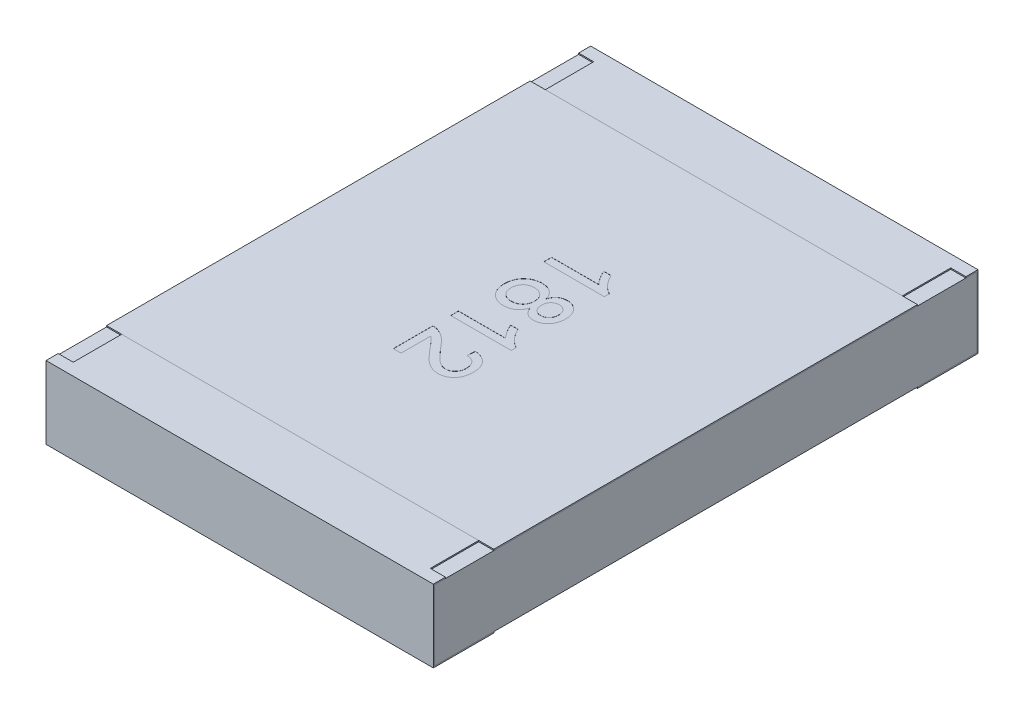
SolidWorks part; units mm, degrees
ref_plane "Front Plane" through (0, 0, 0) normal (0, 0, 1) x (1, 0, 0)
ref_plane "Top Plane" through (0, 0, 0) normal (0, 1, 0) x (1, 0, 0)
ref_plane "Right Plane" through (0, 0, 0) normal (1, 0, 0) x (0, 0, -1)
sketch "Sketch4" plane through (0, 0, 0) normal (1, 0, 0) x (0, 0, -1)
  line L0 (0, 0.1169) -> (0, -0.0721) construction
  line L1 (-2.25, 0) -> (0.3788, 0) construction
  line L2 (-2.25, 0.3) -> (-2.25, -0.3)
  line L3 (-2.25, -0.3) -> (-1.75, -0.3)
  line L4 (-1.75, 0.3) -> (-1.75, 0.29)
  line L5 (-1.75, 0.29) -> (-2.24, 0.29)
  line L6 (-2.24, 0.29) -> (-2.24, -0.29)
  line L7 (-2.24, -0.29) -> (-1.75, -0.29)
  line L8 (-1.75, -0.29) -> (-1.75, -0.3)
  line L9 (-1.75, 0.3) -> (-2.25, 0.3)
  line L10 (1.75, 0.3) -> (2.25, 0.3)
  line L11 (1.75, -0.29) -> (1.75, -0.3)
  line L12 (2.24, -0.29) -> (1.75, -0.29)
  line L13 (2.24, 0.29) -> (2.24, -0.29)
  line L14 (1.75, 0.29) -> (2.24, 0.29)
  line L15 (1.75, 0.3) -> (1.75, 0.29)
  line L16 (2.25, -0.3) -> (1.75, -0.3)
  line L17 (2.25, 0.3) -> (2.25, -0.3)
  dimension "LENGTH" = 2.25
  dimension "HEIGHT" = 0.6
  dimension "END CAP TOP LENGTH" = 0.5
  dimension "END CAP BOTTOM LENGTH" = 0.5
  dimension "D5" = 0.01
  dimension "D6" = 0.01
extrude "Boss-Extrude2" add sketch "Sketch4" along normal mid plane 3.2
sketch "Sketch5" plane through (0, 0, 0) normal (1, 0, 0) x (0, 0, -1)
  line L1 (-2.24, 0.29) -> (2.24, 0.29)
  line L2 (-2.24, 0.29) -> (-2.24, -0.29)
  line L3 (-2.24, -0.29) -> (2.24, -0.29)
  line L4 (2.24, 0.29) -> (2.24, -0.29)
extrude "Boss-Extrude3" add sketch "Sketch5" along normal up to surface and the other way up to surface separate body
sketch "Sketch6" plane through (0, 0.3, 0) normal (0, 1, 0) x (1, 0, 0)
  line L0 (-1.6, 2.25) -> (-1.6, 1.75) construction
  line L1 (-1.6, 2.15) -> (-1.475, 2.15)
  line L2 (-1.6, 2.15) -> (-1.6, 1.75)
  line L3 (-1.6, 1.75) -> (-1.475, 1.75)
  line L4 (-1.475, 2.15) -> (-1.475, 1.75)
  line L5 (1.6, 1.75) -> (-1.6, 1.75) construction
  line L6 (0, 0.0345) -> (0, -0.0345) construction
  line L7 (-0.0325, 0) -> (0.03, 0) construction
  line L8 (1.6, 2.15) -> (1.6, 1.75)
  line L9 (1.6, 1.75) -> (1.475, 1.75)
  line L10 (1.475, 2.15) -> (1.475, 1.75)
  line L11 (1.6, 2.15) -> (1.475, 2.15)
  line L12 (1.6, -2.15) -> (1.475, -2.15)
  line L13 (1.6, -2.15) -> (1.6, -1.75)
  line L14 (1.6, -1.75) -> (1.475, -1.75)
  line L15 (1.475, -2.15) -> (1.475, -1.75)
  line L16 (-1.6, -2.15) -> (-1.475, -2.15)
  line L17 (-1.6, -2.15) -> (-1.6, -1.75)
  line L18 (-1.6, -1.75) -> (-1.475, -1.75)
  line L19 (-1.475, -2.15) -> (-1.475, -1.75)
  dimension "TOP CUT WIDTH" = 0.125
  dimension "TOP CUT LENGTH" = 0.4
extrude "Cut-Extrude1" cut sketch "Sketch6" against normal up to surface (0.01 mm away) up to face at (0, 0.29, 0)
sketch "Sketch7" plane through (0, 0.29, 0) normal (0, 1, 0) x (1, 0, 0)
  line L1 (-1.6, 1.75) -> (1.6, 1.75)
  line L2 (-1.6, 1.75) -> (-1.6, -1.75)
  line L3 (-1.6, -1.75) -> (1.6, -1.75)
  line L4 (1.6, 1.75) -> (1.6, -1.75)
  line L5 (1.475, -1.75) -> (-1.475, -1.75) construction
  line L6 (1.475, 1.75) -> (-1.475, 1.75) construction
  line L7 (-1.6, -2.24) -> (-1.6, 2.24) construction
  line L8 (1.6, 2.24) -> (1.6, -2.24) construction
extrude "Boss-Extrude4" add sketch "Sketch7" along normal up to surface (0.01 mm away) separate body up to face at (0, 0.3, -2.075)
sketch "PART NUMBER" plane through (0, 0.3, 0) normal (0, 1, 0) x (1, 0, 0)
  line L0 (-0.0246, 0.1) -> (-0.0246, -0.1) construction
  line L1 (0, 0) -> (-0.0246, 0) construction
  text T0 "01005" font "Arial" height 0.05
  dimension "D1" = 0.2
sketch "Sketch8" plane through (0, 0.3, 0) normal (0, 1, 0) x (1, 0, 0)
  line L0 (-0.0304, 0.1057) -> (-0.0304, -0.1057) construction
  line L1 (0, 0) -> (-0.0304, 0) construction
  text T0 "0201" font "Arial" height 0.06
sketch "Sketch9" plane through (0, 0.3, 0) normal (0, 1, 0) x (1, 0, 0)
  line L0 (-0.0372, 0.139) -> (-0.0372, -0.139) construction
  line L1 (-0.0372, 0) -> (0, 0) construction
  text T0 "0402" font "Arial" height 0.08
sketch "Sketch10" plane through (0, 0.3, 0) normal (0, 1, 0) x (1, 0, 0)
  line L0 (-0.125, 0.425) -> (-0.125, -0.425) construction
  line L1 (0, 0) -> (-0.125, 0) construction
  text T0 "0603" font "Arial" height 0.25
  dimension "D1" = 0.125
  dimension "D2" = 0.85
sketch "Sketch11" plane through (0, 0.3, 0) normal (0, 1, 0) x (1, 0, 0)
  line L0 (0, 0) -> (-0.15, 0) construction
  line L1 (-0.15, 0.515) -> (-0.15, -0.515) construction
  text T0 "0805" font "Arial" height 0.3
  dimension "D1" = 0.15
sketch "Sketch12" plane through (0, 0.3, 0) normal (0, 1, 0) x (1, 0, 0)
  line L0 (-0.15, 0.5423) -> (-0.15, -0.5423) construction
  line L1 (0, 0) -> (-0.15, 0) construction
  text T0 "1206" font "Arial" height 0.3
  dimension "D1" = 0.15
sketch "Sketch13" plane through (0, 0.3, 0) normal (0, 1, 0) x (1, 0, 0)
  line L0 (-0.15, 0.5735) -> (-0.15, -0.5735) construction
  line L1 (0, 0) -> (-0.15, 0) construction
  text T0 "1210" font "Arial" height 0.3
  dimension "D1" = 0.15
sketch "Sketch14" plane through (0, 0.3, 0) normal (0, 1, 0) x (1, 0, 0)
  line L0 (-0.25, 0.8778) -> (-0.25, -0.8778) construction
  line L1 (0, 0) -> (-0.25, 0) construction
  text T0 "1812" font "Arial" height 0.5
  dimension "D1" = 0.25
extrude "TEXT1812" cut sketch "Sketch14" against normal blind 0.001
sketch "Sketch15" plane through (0, 0.3, 0) normal (0, 1, 0) x (1, 0, 0)
  line L0 (-0.25, 0.9382) -> (-0.25, -0.9382) construction
  line L1 (0, 0) -> (-0.25, 0) construction
  text T0 "2010" font "Arial" height 0.5
  dimension "D1" = 0.25
sketch "Sketch16" plane through (0, 0.3, 0) normal (0, 1, 0) x (1, 0, 0)
  line L0 (-0.25, 1.4279) -> (-0.25, -1.4279) construction
  line L1 (0, 0) -> (-0.25, 0) construction
  text T0 "2512" font "Arial" height 0.5
  dimension "D1" = 0.25
